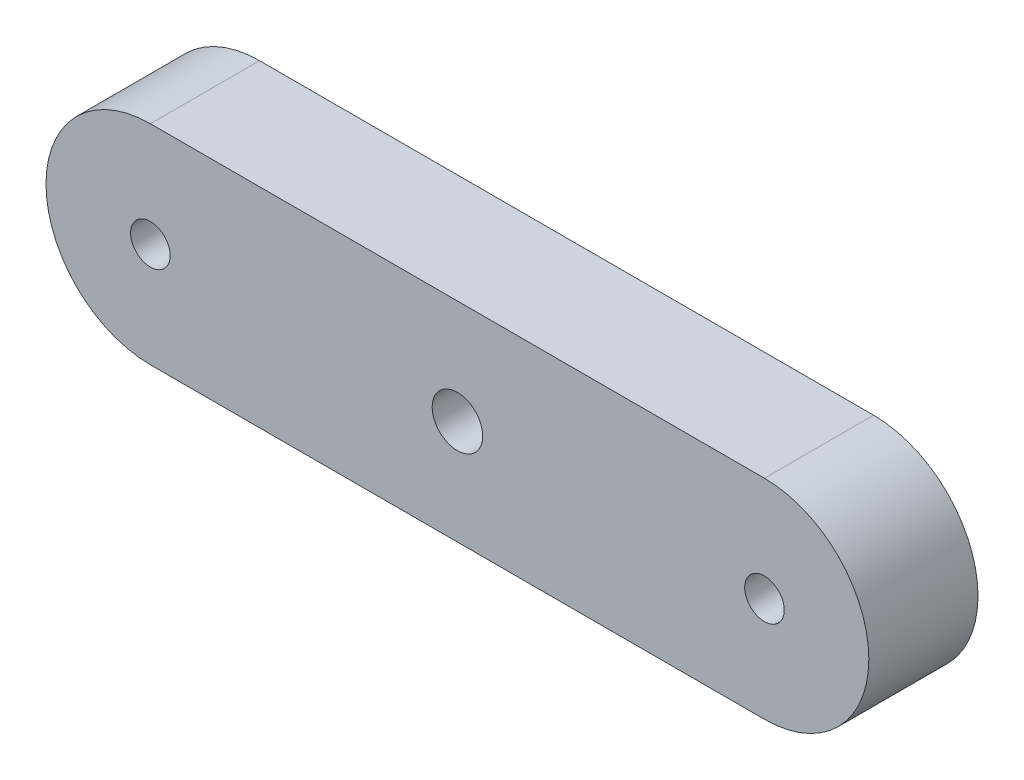
SolidWorks part; units mm, degrees
ref_plane "Спереди" through (0, 0, 0) normal (0, 0, 1) x (1, 0, 0)
ref_plane "Сверху" through (0, 0, 0) normal (0, 1, 0) x (1, 0, 0)
ref_plane "Справа" through (0, 0, 0) normal (1, 0, 0) x (0, 0, -1)
sketch "Эскиз1" plane through (0, 0, 0) normal (0, 0, 1) x (1, 0, 0)
  line L0 (0, 0) -> (45, 0) construction
  line L1 (0, 0) -> (45, 0) construction
  line L2 (0, 7.65) -> (45, 7.65)
  line L3 (0, -7.65) -> (45, -7.65)
  circle A0 centre (0, 0) radius 1.45
  circle A1 centre (45, 0) radius 1.45
  circle A2 centre (22.5, 0) radius 5.15
  arc A3 (0, 7.65) -> (0, -7.65) centre (0, 0) ccw
  arc A4 (45, -7.65) -> (45, 7.65) centre (45, 0) ccw
  point P7 (22.5, 0)
  dimension "D1" = 2.9
  dimension "D2" = 10.3
  dimension "D3" = 45
  dimension "D4" = 15.3
extrude "Бобышка-Вытянуть1" add sketch "Эскиз1" along normal blind 8
sketch "Эскиз2" plane through (0, 0, 0) normal (0, 0, -1) x (-1, 0, 0)
  circle A0 centre (-22.5, 0) radius 5.3054
  circle A1 centre (-22.5, 0) radius 1.85
  dimension "D1" = 3.7
extrude "Бобышка-Вытянуть2" add sketch "Эскиз2" against normal up to surface (8 mm away) up to face at (46.45, 0, 8)
